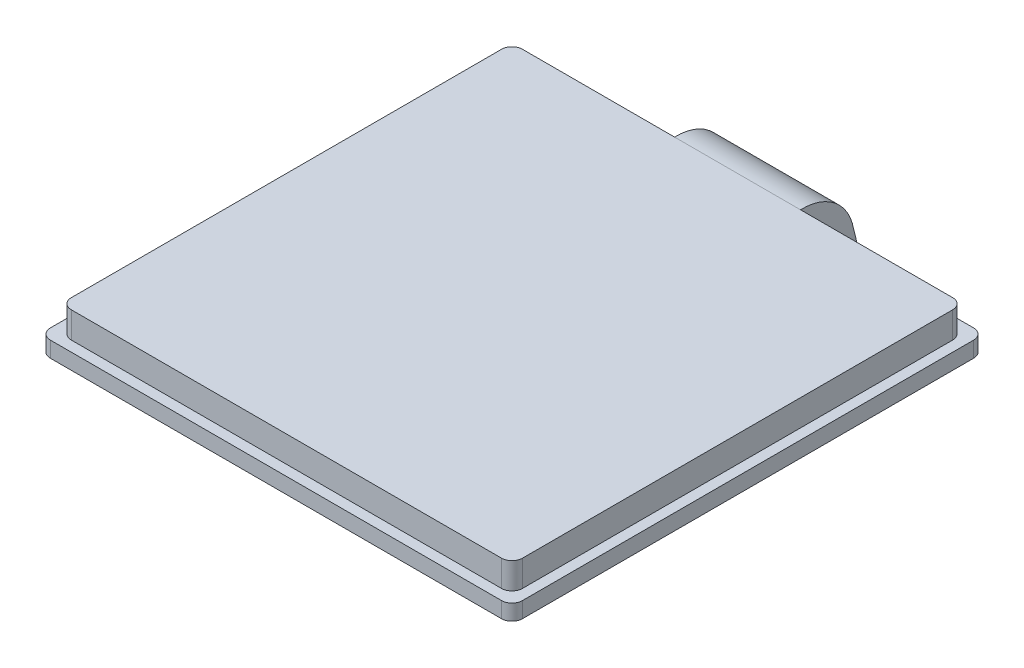
SolidWorks part; units mm, degrees
ref_plane "Front Plane" through (0, 0, 0) normal (0, 0, 1) x (1, 0, 0)
ref_plane "Top Plane" through (0, 0, 0) normal (0, 1, 0) x (1, 0, 0)
ref_plane "Right Plane" through (0, 0, 0) normal (1, 0, 0) x (0, 0, -1)
sketch "Sketch1" plane through (0, 0, 0) normal (0, 1, 0) x (1, 0, 0)
  line L1 (-205, 215) -> (205, 215)
  line L2 (-215, 205) -> (-215, -205)
  line L3 (-205, -215) -> (205, -215)
  line L4 (215, 205) -> (215, -205)
  line L5 (-215, 225) -> (215, 225)
  line L6 (-225, 215) -> (-225, -215)
  line L7 (-215, -225) -> (215, -225)
  line L8 (225, 215) -> (225, -215)
  arc A0 (-215, -205) -> (-205, -215) centre (-205, -205) ccw
  arc A1 (205, -215) -> (215, -205) centre (205, -205) ccw
  arc A2 (205, 215) -> (215, 205) centre (205, 205) cw
  arc A3 (-205, 215) -> (-215, 205) centre (-205, 205) ccw
  arc A4 (-225, -215) -> (-215, -225) centre (-215, -215) ccw
  arc A5 (215, -225) -> (225, -215) centre (215, -215) ccw
  arc A6 (215, 225) -> (225, 215) centre (215, 215) cw
  arc A7 (-215, 225) -> (-225, 215) centre (-215, 215) ccw
  point P7 (-215, -215)
  point P10 (215, -215)
  point P13 (215, 215)
  dimension "D5" = 10
  dimension "D10" = 10
  dimension "D1" = 430
  dimension "D2" = 430
  dimension "D3" = 215
  dimension "D4" = 215
  dimension "D6" = 10
  dimension "D7" = 10
  dimension "D8" = 10
  dimension "D9" = 10
extrude "Boss-Extrude1" add sketch "Sketch1" along normal blind 15
sketch "Sketch2" plane through (0, 15, 0) normal (0, 1, 0) x (1, 0, 0)
  line L0 (-205, -215) -> (205, -215) construction
  line L1 (-215, 205) -> (-215, -205) construction
  line L2 (205, 215) -> (-205, 215) construction
  line L3 (215, -205) -> (215, 205) construction
  line L4 (-205, -215) -> (205, -215)
  line L5 (-215, 205) -> (-215, -205)
  line L6 (205, 215) -> (-205, 215)
  line L7 (215, -205) -> (215, 205)
  arc A0 (205, -215) -> (215, -205) centre (205, -205) ccw construction
  arc A1 (-215, -205) -> (-205, -215) centre (-205, -205) ccw construction
  arc A2 (-205, 215) -> (-215, 205) centre (-205, 205) ccw construction
  arc A3 (215, 205) -> (205, 215) centre (205, 205) ccw construction
  arc A4 (205, -215) -> (215, -205) centre (205, -205) ccw
  arc A5 (-215, -205) -> (-205, -215) centre (-205, -205) ccw
  arc A6 (-205, 215) -> (-215, 205) centre (-205, 205) ccw
  arc A7 (215, 205) -> (205, 215) centre (205, 205) ccw
extrude "Boss-Extrude2" add sketch "Sketch2" along normal blind 25 separate body
shell "Shell1" thickness 5
sketch "Sketch3" plane through (0, 0, 0) normal (1, 0, 0) x (0, 0, -1)
  line L1 (264.297, 4.2126) -> (271.2849, -24.38)
  line L8 (215, 40) -> (215, 15)
  circle A0 centre (251.2849, -20) radius 10
  arc A2 (215, 40) -> (264.297, 4.2126) centre (216.8639, -9.2793) cw
  arc A3 (233.2062, -13.4461) -> (215, 15) centre (224.1031, 0.7769) ccw
  arc A4 (233.2062, -13.4461) -> (271.2849, -24.38) centre (252.0095, -19.735) ccw
  point P6 (233.2062, -13.4461)
  point P12 (0, 0)
  dimension "D4" = 20
  dimension "D6" = 20
extrude "Boss-Extrude9" add sketch "Sketch3" along normal blind 60 and the other way blind 60 separate body
sketch "Sketch4" plane through (0, 0, 0) normal (0, 0, 1) x (1, 0, 0)
  line L7 (-40, -0.6596) -> (40, -0.6596)
  line L8 (-40, -0.6596) -> (-40, -45.8016)
  line L9 (-40, -45.8016) -> (40, -45.8016)
  line L10 (40, -0.6596) -> (40, -45.8016)
  point P4 (0, 0)
  dimension "D1" = 40
  dimension "D2" = 40
extrude "Cut-Extrude2" cut sketch "Sketch4" against normal blind 377
